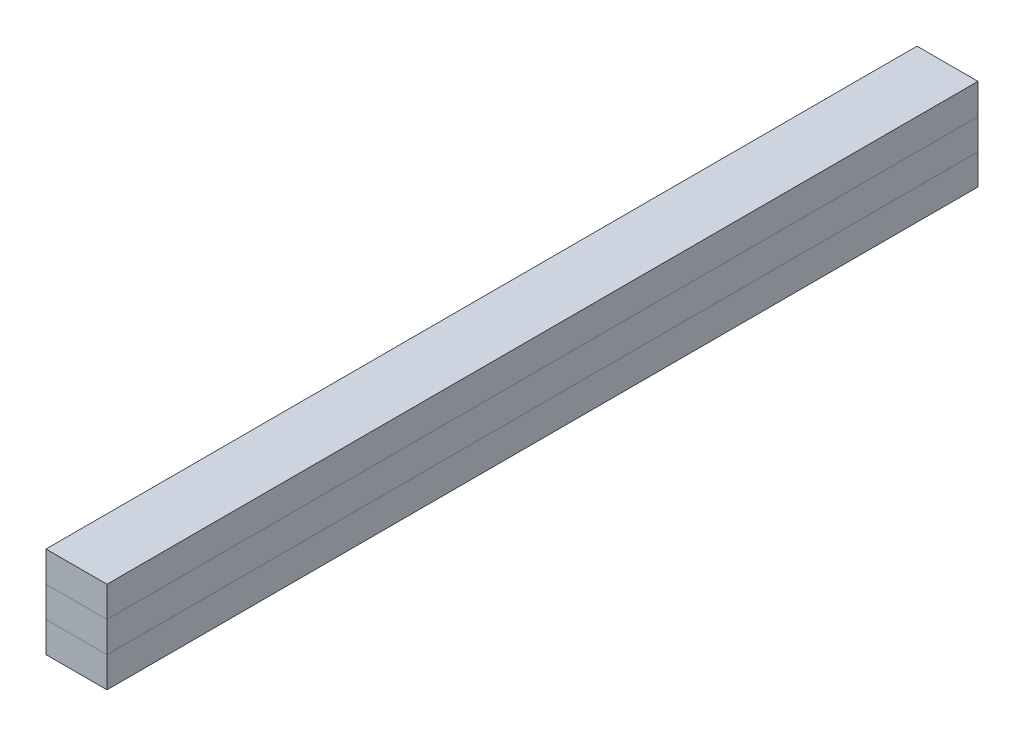
SolidWorks part; units mm, degrees
ref_plane "Płaszczyzna przednia" through (0, 0, 0) normal (0, 0, 1) x (1, 0, 0)
ref_plane "Płaszczyzna górna" through (0, 0, 0) normal (0, 1, 0) x (1, 0, 0)
ref_plane "Płaszczyzna prawa" through (0, 0, 0) normal (1, 0, 0) x (0, 0, -1)
sketch "Szkic1" plane through (0, 0, 0) normal (0, 0, 1) x (1, 0, 0)
  line L0 (0, 14) -> (14, 14)
  line L1 (0, 0) -> (14, 0)
  line L2 (0, 0) -> (0, 21)
  line L3 (0, 21) -> (14, 21)
  line L4 (14, 0) -> (14, 21)
  line L5 (0, 7) -> (14, 7)
  dimension "D1" = 7
  dimension "D2" = 7
  dimension "D3" = 21
  dimension "D4" = 14
extrude "Dodanie-wyciągnięcie2" add sketch "Szkic1" along normal blind 200 contours L4 L3 L2 L1
sketch "Szkic2" plane through (0, 0, 0) normal (0, 0, 1) x (1, 0, 0)
  line L0 (0, 14) -> (14, 14)
  line L1 (0, 21) -> (14, 21)
  line L2 (0, 21) -> (0, 0)
  line L3 (0, 0) -> (14, 0)
  line L4 (14, 21) -> (14, 0)
  line L5 (0, 7) -> (14, 7)
  dimension "D1" = 7
  dimension "D2" = 7
split "Podziel1" trim tools "Szkic2" bodies to split 103 resulting bodies 104 105 106
